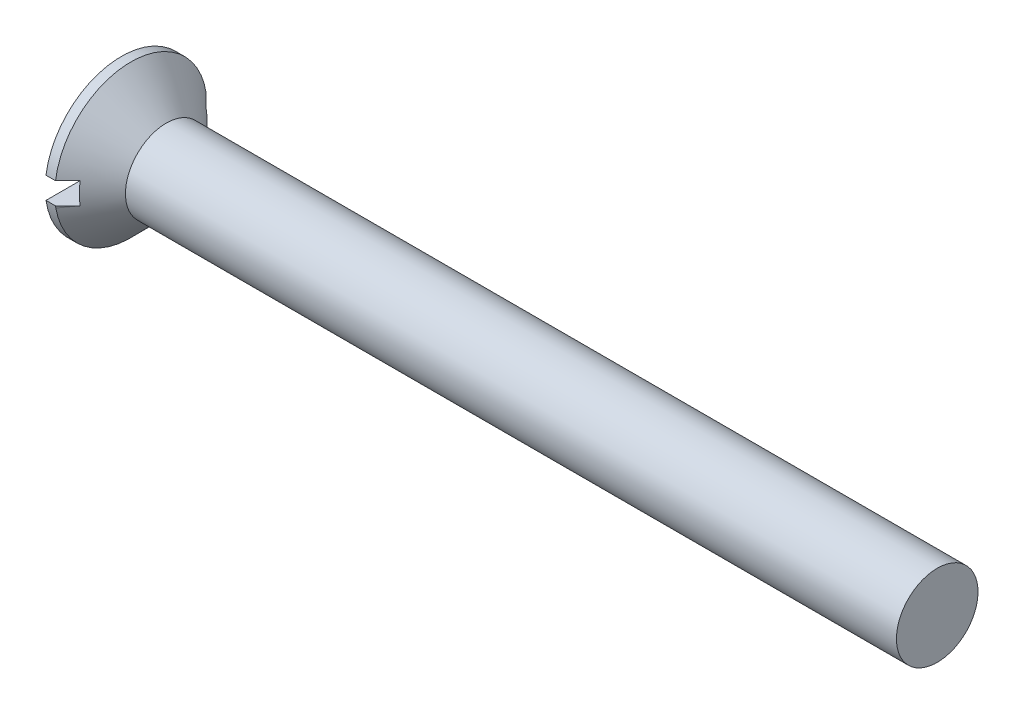
SolidWorks part; units mm, degrees
material "Plain Carbon Steel"
ref_plane "Front Plane" through (0, 0, 0) normal (0, 0, 1) x (1, 0, 0)
ref_plane "Top Plane" through (0, 0, 0) normal (0, 1, 0) x (1, 0, 0)
ref_plane "Right Plane" through (0, 0, 0) normal (1, 0, 0) x (0, 0, -1)
sketch "Sketch1" plane through (0, 0, 0) normal (0, 0, 1) x (1, 0, 0)
  line L0 (0, 0) -> (0, 2.8)
  line L1 (0, 2.8) -> (0.35, 2.8)
  line L2 (0.35, 2.8) -> (1.65, 1.5)
  line L3 (1.65, 1.5) -> (30, 1.5)
  line L4 (30, 1.5) -> (30, 0)
  line L5 (30, 0) -> (0, 0) construction
  line L6 (0, 0) -> (30, 0)
  dimension "D1" = 45
  dimension "D2" = 3
  dimension "D3" = 5.6
  dimension "D4" = 1.65
  dimension "D5" = 30
revolve "Revolve1" add sketch "Sketch1" angle 360 about L5
sketch "Sketch2" plane through (0, 0, 0) normal (-1, 0, 0) x (0, 0, 1)
  line L0 (2.8, 0) -> (-2.8, 0) construction
  line L1 (-2.8, 0.4) -> (2.8, 0.4)
  line L2 (-2.8, 0.4) -> (-2.8, -0.4)
  line L3 (-2.8, -0.4) -> (2.8, -0.4)
  line L4 (2.8, 0.4) -> (2.8, -0.4)
  circle A0 centre (0, 0) radius 2.8 construction
  dimension "D1" = 0.8
extrude "Cut-Extrude1" cut sketch "Sketch2" against normal blind 0.8
